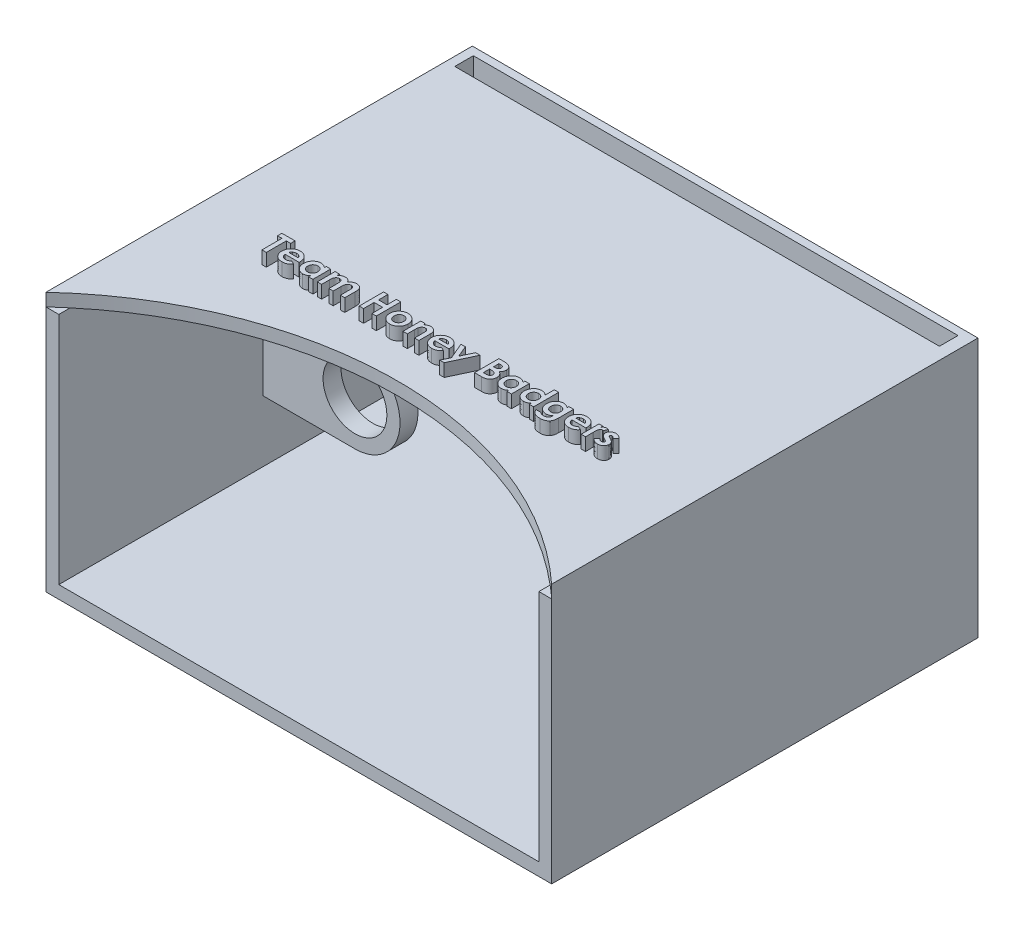
SolidWorks part; units mm, degrees
ref_plane "Front Plane" through (0, 0, 0) normal (0, 0, 1) x (1, 0, 0)
ref_plane "Top Plane" through (0, 0, 0) normal (0, 1, 0) x (1, 0, 0)
ref_plane "Right Plane" through (0, 0, 0) normal (1, 0, 0) x (0, 0, -1)
sketch "Sketch1" plane through (0, 0, 0) normal (0, 0, 1) x (1, 0, 0)
  line L1 (0, 0) -> (394.9267, 0)
  line L2 (0, 0) -> (0, 202.7697)
  line L3 (0, 202.7697) -> (394.9267, 202.7697)
  line L4 (394.9267, 0) -> (394.9267, 202.7697)
extrude "Boss-Extrude1" add sketch "Sketch1" along normal blind 333
shell "Shell5" thickness 10
ref_plane "Plane2" through (0, 0, 166.5) normal (0, 0, 1) x (1, 0, 0)
sketch "Sketch18" plane through (0, 0, 166.5) normal (0, 0, 1) x (1, 0, 0)
  line L0 (10, 128.3559) -> (81.8144, 128.3559)
  line L1 (10, 192.7697) -> (10, 10) construction
  line L2 (81.8144, 57.9602) -> (10, 57.9602)
  line L3 (10, 192.7697) -> (10, 10) construction
  line L4 (10, 57.9602) -> (10, 128.3559)
  arc A0 (81.8144, 128.3559) -> (81.8144, 57.9602) centre (81.8144, 93.1581) cw
extrude "Boss-Extrude2" add sketch "Sketch18" along normal mid plane 14
sketch "Sketch19" plane through (0, 0, 173.5) normal (0, 0, 1) x (1, 0, 0)
  circle A0 centre (81.8144, 93.1581) radius 24.923
  arc A1 (81.8144, 57.9602) -> (81.8144, 128.3559) centre (81.8144, 93.1581) ccw construction
extrude "Cut-Extrude1" cut sketch "Sketch19" against normal blind 14
sketch "Sketch22" plane through (0, 0, 166.5) normal (0, 0, 1) x (1, 0, 0)
  line L0 (384.9267, 128.3559) -> (291.109, 128.3559)
  line L1 (384.9267, 10) -> (384.9267, 192.7697) construction
  line L2 (291.109, 59.382) -> (384.9267, 59.382)
  line L3 (384.9267, 59.382) -> (384.9267, 128.3559)
  arc A0 (291.109, 128.3559) -> (291.109, 59.382) centre (291.109, 93.869) ccw
extrude "Boss-Extrude3" add sketch "Sketch22" along normal mid plane 14
sketch "Sketch23" plane through (0, 0, 173.5) normal (0, 0, 1) x (1, 0, 0)
  circle A0 centre (291.109, 93.869) radius 24.923
  circle A1 centre (81.8144, 93.1581) radius 24.923 construction
  arc A2 (291.109, 128.3559) -> (291.109, 59.382) centre (291.109, 93.869) ccw construction
extrude "Cut-Extrude2" cut sketch "Sketch23" against normal blind 14
sketch "Sketch24" plane through (0, 202.7697, 0) normal (0, 1, 0) x (1, 0, 0)
  line L2 (6.9001, -6.123) -> (385.4501, -6.123)
  line L3 (6.9001, -6.123) -> (6.9001, -20.6542)
  line L4 (6.9001, -20.6542) -> (385.4501, -20.6542)
  line L5 (385.4501, -6.123) -> (385.4501, -20.6542)
extrude "Cut-Extrude6" cut sketch "Sketch24" against normal blind 30
sketch "Sketch25" plane through (0, 10, 0) normal (0, 1, 0) x (1, 0, 0)
  line L1 (6.9001, -20.6542) -> (32.8949, -20.6542)
  line L2 (6.9001, -20.6542) -> (6.9001, -31.5401)
  line L3 (6.9001, -31.5401) -> (32.8949, -31.5401)
  line L4 (32.8949, -20.6542) -> (32.8949, -31.5401)
extrude "Boss-Extrude5" add sketch "Sketch25" along normal blind 14
sketch "Sketch27" plane through (0, 10, 0) normal (0, 1, 0) x (1, 0, 0)
  line L1 (385.4501, -20.6542) -> (355.9714, -20.6542)
  line L2 (385.4501, -20.6542) -> (385.4501, -34.795)
  line L3 (385.4501, -34.795) -> (355.9714, -34.795)
  line L4 (355.9714, -20.6542) -> (355.9714, -34.795)
extrude "Boss-Extrude7" add sketch "Sketch27" along normal blind 14
sketch "Sketch33" plane through (0, 192.7697, 0) normal (0, -1, 0) x (1, 0, 0)
  line L0 (197.4633, 10) -> (197.4633, 132.0715)
  line L1 (10, 10) -> (384.9267, 10) construction
extrude "Extrude-Thin2" add sketch "Sketch33" along normal up to next thin contours L0
sketch "Sketch34" plane through (197.4633, 0, 0) normal (-1, 0, 0) x (0, 0, 1)
  line L0 (132.0715, 58.1579) -> (39.5152, 10)
  line L1 (132.0715, 10) -> (132.0715, 192.7697) construction
  line L2 (132.0715, 10) -> (10, 10) construction
  line L3 (39.5152, 10) -> (132.0715, 10)
  line L4 (132.0715, 10) -> (132.0715, 58.1579)
extrude "Cut-Extrude8" cut sketch "Sketch34" against normal blind 49
sketch "Sketch35" plane through (0, 192.7697, 0) normal (0, 1, 0) x (1, 0, 0)
  line L1 (197.4633, -10) -> (207.4633, -10)
  line L2 (197.4633, -10) -> (197.4633, -20.6542)
  line L3 (197.4633, -20.6542) -> (207.4633, -20.6542)
  line L4 (207.4633, -10) -> (207.4633, -20.6542)
extrude "Cut-Extrude11" cut sketch "Sketch35" against normal up to surface (182.7697 mm away) up to face at (197.9558, 10, 62.5198)
sketch "Sketch37" plane through (0, 202.7697, 0) normal (0, 1, 0) x (1, 0, 0)
  text T0 "Team Honey Badgers " font "Century Gothic" height in points 72
extrude "Boss-Extrude9" add sketch "Sketch37" along normal blind 10
sketch "Sketch38" plane through (0, 202.7697, 0) normal (0, 1, 0) x (1, 0, 0)
  line L0 (0, -333) -> (394.9267, -333)
  arc A0 (0, -333) -> (394.9267, -333) centre (197.4633, -546.5971) cw
extrude "Cut-Extrude12" cut sketch "Sketch38" against normal blind 10
